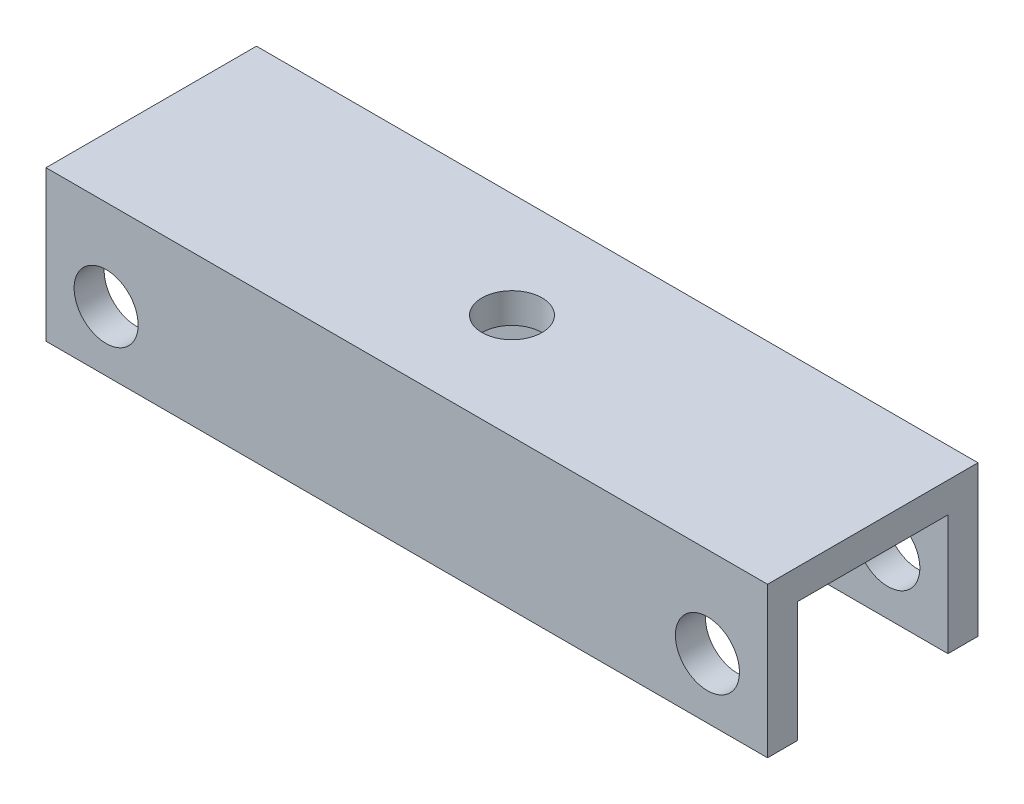
SolidWorks part; units mm, degrees
ref_plane "Front Plane" through (0, 0, 0) normal (0, 0, 1) x (1, 0, 0)
ref_plane "Top Plane" through (0, 0, 0) normal (0, 1, 0) x (1, 0, 0)
ref_plane "Right Plane" through (0, 0, 0) normal (1, 0, 0) x (0, 0, -1)
sketch "Sketch6" plane through (0, 0, 0) normal (1, 0, 0) x (0, 0, -1)
  line L0 (-35.0487, 0) -> (9.4013, 0)
  line L1 (9.4013, 0) -> (9.4013, -31.75)
  line L2 (9.4013, -31.75) -> (3.0513, -31.75)
  line L3 (3.0513, -31.75) -> (3.0513, -6.35)
  line L4 (3.0513, -6.35) -> (-28.6987, -6.35)
  line L5 (-28.6987, -6.35) -> (-28.6987, -31.75)
  line L6 (-28.6987, -31.75) -> (-35.0487, -31.75)
  line L7 (-35.0487, -31.75) -> (-35.0487, 0)
  dimension "D1" = 31.75
  dimension "D2" = 44.45
  dimension "D3" = 6.35
  dimension "D4" = 31.75
  dimension "D5" = 6.35
  dimension "D6" = 31.75
extrude "Boss-Extrude3" add sketch "Sketch6" along normal blind 152.4
sketch "Sketch7" plane through (0, 0, 0) normal (0, 1, 0) x (1, 0, 0)
  line L0 (152.4, 9.4013) -> (0, 9.4013) construction
  line L1 (152.4, 9.4013) -> (152.4, -35.0487) construction
  circle A0 centre (76.2, -12.8237) radius 6.35
  dimension "D1" = 22.225
  dimension "D2" = 76.2
extrude "Cut-Extrude3" cut sketch "Sketch7" against normal up to next
sketch "Sketch8" plane through (0, 0, 35.0487) normal (0, 0, 1) x (1, 0, 0)
  line L0 (0, 0) -> (0, -31.75) construction
  line L1 (152.4, -31.75) -> (0, -31.75) construction
  line L2 (76.2, -31.75) -> (76.2, 31.7574) construction
  line L3 (152.4, 0) -> (0, 0) construction
  circle A0 centre (12.7, -19.05) radius 6.7633
  circle A1 centre (139.7, -19.05) radius 6.7633
  dimension "D1" = 12.7
  dimension "D2" = 19.05
extrude "Cut-Extrude4" cut sketch "Sketch8" against normal through all
